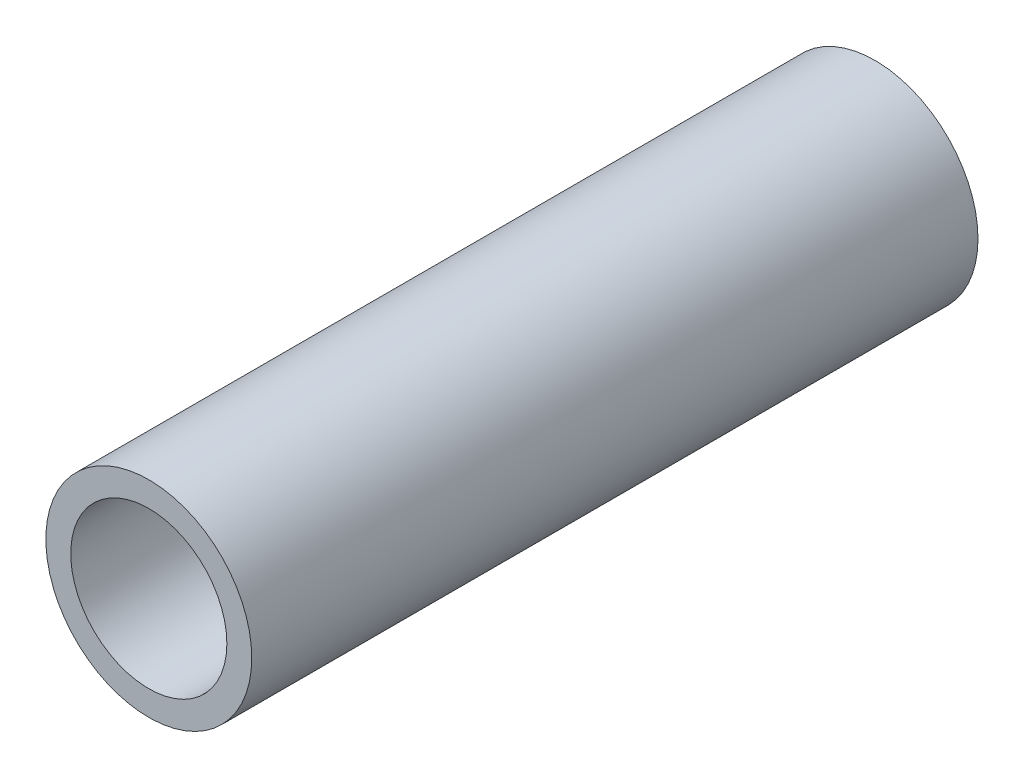
SolidWorks part; units mm, degrees
material "Galvanized Steel"
ref_plane "Front Plane" through (0, 0, 0) normal (0, 0, 1) x (1, 0, 0)
ref_plane "Top Plane" through (0, 0, 0) normal (0, 1, 0) x (1, 0, 0)
ref_plane "Right Plane" through (0, 0, 0) normal (1, 0, 0) x (0, 0, -1)
sketch "Sketch12" plane through (0, 0, 0) normal (0, 0, 1) x (1, 0, 0)
  circle A0 centre (0, 0) radius 259.265
  circle A1 centre (0, 0) radius 196.6
  dimension "D1" = 393.2
  dimension "D2" = 518.53
extrude "Boss-Extrude1" add sketch "Sketch12" along normal blind 1828.8
